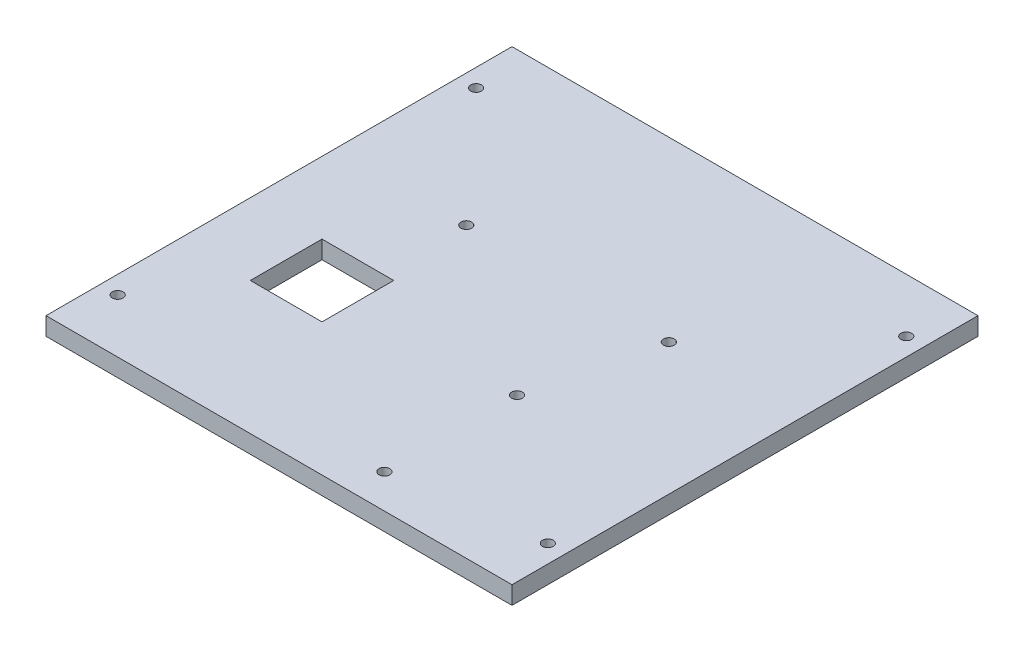
SolidWorks part; units mm, degrees
ref_plane "Front Plane" through (0, 0, 0) normal (0, 0, 1) x (1, 0, 0)
ref_plane "Top Plane" through (0, 0, 0) normal (0, 1, 0) x (1, 0, 0)
ref_plane "Right Plane" through (0, 0, 0) normal (1, 0, 0) x (0, 0, -1)
sketch "Sketch1" plane through (0, 0, 0) normal (0, 1, 0) x (1, 0, 0)
  line L1 (-65, 65) -> (65, 65)
  line L2 (-65, 65) -> (-65, -65)
  line L3 (-65, -65) -> (65, -65)
  line L4 (65, 65) -> (65, -65)
  line L5 (-65, 65) -> (65, -65) construction
  line L6 (-65, -65) -> (65, 65) construction
  point P0 (0, 0)
  dimension "D1" = 130
extrude "Boss-Extrude1" add sketch "Sketch1" along normal blind 5
sketch "Sketch2" plane through (0, 0, 0) normal (0, -1, 0) x (1, 0, 0)
  circle A0 centre (19.9, 55.5) radius 1.5
  circle A1 centre (19.9, 18.5) radius 1.5
  dimension "D1" = 3
  dimension "D2" = 3
extrude "Cut-Extrude1" cut sketch "Sketch2" against normal up to surface (5 mm away) up to face at (0, 5, 0)
sketch "Sketch3" plane through (0, 5, 0) normal (0, 1, 0) x (1, 0, 0)
  circle A0 centre (-28.25, 15.5) radius 1.5
  circle A1 centre (28.25, 15.5) radius 1.5
  dimension "D1" = 3
  dimension "D2" = 3
extrude "Cut-Extrude2" cut sketch "Sketch3" against normal up to surface (5 mm away) up to face at (19.9, 0, 54)
sketch "Sketch4" plane through (0, 5, 0) normal (0, 1, 0) x (1, 0, 0)
  line L1 (65, 65) -> (-65, 65) construction
  line L4 (0, 65) -> (0, -65) construction
  line L5 (-65, -65) -> (65, -65) construction
  line L6 (-65, 0) -> (65, 0) construction
  line L7 (-65, 65) -> (-65, -65) construction
  line L8 (65, -65) -> (65, 65) construction
  circle A0 centre (-60, 50) radius 1.5
  circle A1 centre (60, 50) radius 1.5
  circle A2 centre (60, -50) radius 1.5
  circle A3 centre (-60, -50) radius 1.5
  dimension "D1" = 3
  dimension "D2" = 60
  dimension "D3" = 50
extrude "Cut-Extrude3" cut sketch "Sketch4" against normal up to surface (5 mm away) up to face at (-28.25, 0, -14)
sketch "Sketch5" plane through (0, 5, 0) normal (0, 1, 0) x (1, 0, 0)
  line L1 (-45, -8) -> (-25, -8)
  line L2 (-45, -8) -> (-45, -28)
  line L3 (-45, -28) -> (-25, -28)
  line L4 (-25, -8) -> (-25, -28)
  line L5 (-45, -8) -> (-25, -28) construction
  line L6 (-45, -28) -> (-25, -8) construction
  point P0 (-35, -18)
  dimension "D1" = 20
  dimension "D2" = 20
  dimension "D3" = 25
  dimension "D4" = 8
extrude "Cut-Extrude4" cut sketch "Sketch5" against normal up to surface (5 mm away) up to face at (-60, 0, -48.5)
